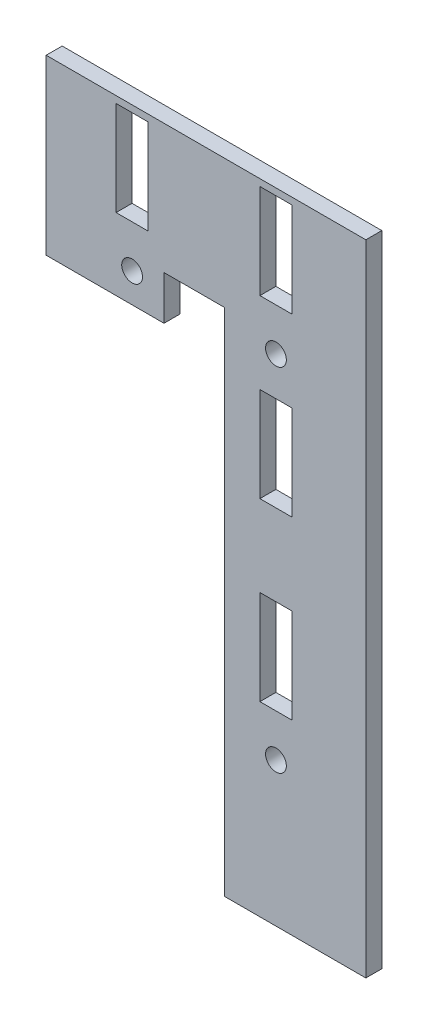
SolidWorks part; units mm, degrees
ref_plane "Front Plane" through (0, 0, 0) normal (1, 0, 0) x (0, 1, 0)
ref_plane "Top Plane" through (0, 0, 0) normal (0, 0, 1) x (0, 1, 0)
ref_plane "Right Plane" through (0, 0, 0) normal (0, 1, 0) x (-1, 0, 0)
sketch "Sketch1" plane through (0, 0, 0) normal (0, 0, 1) x (0, 1, 0)
  line L1 (-50.8, 25.4) -> (50.8, 25.4)
  line L2 (-50.8, 25.4) -> (-50.8, -25.4)
  line L3 (-50.8, -25.4) -> (50.8, -25.4)
  line L4 (50.8, 25.4) -> (50.8, -25.4)
  line L5 (-50.8, 25.4) -> (50.8, -25.4) construction
  line L6 (-50.8, -25.4) -> (50.8, 25.4) construction
  point P0 (0, 0)
  dimension "D1" = 101.6
  dimension "D2" = 50.8
extrude "Boss-Extrude1" add sketch "Sketch1" along normal blind 2.54
sketch "Sketch2" plane through (0, 0, 2.54) normal (0, 0, 1) x (1, 0, 0)
  line L0 (11.1159, -27.94) -> (11.1159, 27.94) construction
  line L1 (11.1159, 27.94) -> (-11.7441, 27.94) construction
  line L2 (-11.7441, 27.94) -> (-11.7441, -27.94) construction
  line L3 (-11.7441, -27.94) -> (11.1159, -27.94) construction
  line L4 (25.4, 50.8) -> (-25.4, 50.8) construction
  circle A0 centre (11.1159, 27.94) radius 1.651
  circle A1 centre (11.1159, -27.94) radius 1.651
  circle A2 centre (-11.7441, 27.94) radius 1.651
  dimension "D3" = 3.302
  dimension "D1" = 55.88
  dimension "D2" = 22.86
  dimension "D4" = 22.86
extrude "Cut-Extrude1" cut sketch "Sketch2" against normal through all
sketch "Sketch3" plane through (0, 0, 2.54) normal (0, 0, 1) x (1, 0, 0)
  line L0 (11.1159, -27.94) -> (11.1159, 27.94) construction
  line L1 (13.6659, -6.16) -> (8.5659, -6.16)
  line L2 (13.6659, -6.16) -> (13.6659, -21.18)
  line L3 (13.6659, -21.18) -> (8.5659, -21.18)
  line L4 (8.5659, -6.16) -> (8.5659, -21.18)
  line L5 (13.6659, -6.16) -> (8.5659, -21.18) construction
  line L6 (13.6659, -21.18) -> (8.5659, -6.16) construction
  line L7 (13.6659, 6.76) -> (8.5659, 6.76)
  line L8 (13.6659, 6.76) -> (13.6659, 21.78)
  line L9 (13.6659, 21.78) -> (8.5659, 21.78)
  line L10 (8.5659, 6.76) -> (8.5659, 21.78)
  line L11 (13.6659, 6.76) -> (8.5659, 21.78) construction
  line L12 (13.6659, 21.78) -> (8.5659, 6.76) construction
  line L13 (13.6659, 34.7) -> (8.5659, 34.7)
  line L14 (13.6659, 34.7) -> (13.6659, 49.72)
  line L15 (13.6659, 49.72) -> (8.5659, 49.72)
  line L16 (8.5659, 34.7) -> (8.5659, 49.72)
  line L17 (13.6659, 34.7) -> (8.5659, 49.72) construction
  line L18 (13.6659, 49.72) -> (8.5659, 34.7) construction
  line L19 (-9.1941, 34.7) -> (-14.2941, 34.7)
  line L20 (-9.1941, 34.7) -> (-9.1941, 49.72)
  line L21 (-9.1941, 49.72) -> (-14.2941, 49.72)
  line L22 (-14.2941, 34.7) -> (-14.2941, 49.72)
  line L23 (-9.1941, 34.7) -> (-14.2941, 49.72) construction
  line L24 (-9.1941, 49.72) -> (-14.2941, 34.7) construction
  circle A0 centre (11.1159, -27.94) radius 1.651 construction
  point P0 (11.1159, -13.67)
  point P10 (11.1159, 14.27)
  point P14 (11.1159, 42.21)
  point P19 (-11.7441, 42.21)
  point P24 (0, 0)
  dimension "D1" = 6.76
  dimension "D3" = 15.02
  dimension "D4" = 27.94
  dimension "D5" = 27.94
  dimension "D6" = 22.86
  dimension "D7" = 5.1
extrude "Cut-Extrude4" cut sketch "Sketch3" against normal through all
sketch "Sketch5" plane through (0, 0, 2.54) normal (0, 0, 1) x (1, 0, 0)
  line L0 (2.9779, -50.8) -> (2.9779, 30.255)
  line L1 (-25.4, -50.8) -> (25.4, -50.8) construction
  line L2 (2.9779, 30.255) -> (-6.6741, 30.255)
  line L3 (-6.6741, 30.255) -> (-6.6741, 23.27)
  line L4 (-6.6741, 23.27) -> (-25.4, 23.27)
  line L5 (-25.4, 50.8) -> (-25.4, -50.8) construction
  line L6 (-25.4, 23.27) -> (-25.4, -50.8)
  line L7 (-25.4, -50.8) -> (2.9779, -50.8)
  dimension "D1" = 5.588
  dimension "D2" = 4.445
  dimension "D3" = 11.43
  dimension "D4" = 15.24
extrude "Cut-Extrude5" cut sketch "Sketch5" against normal through all
